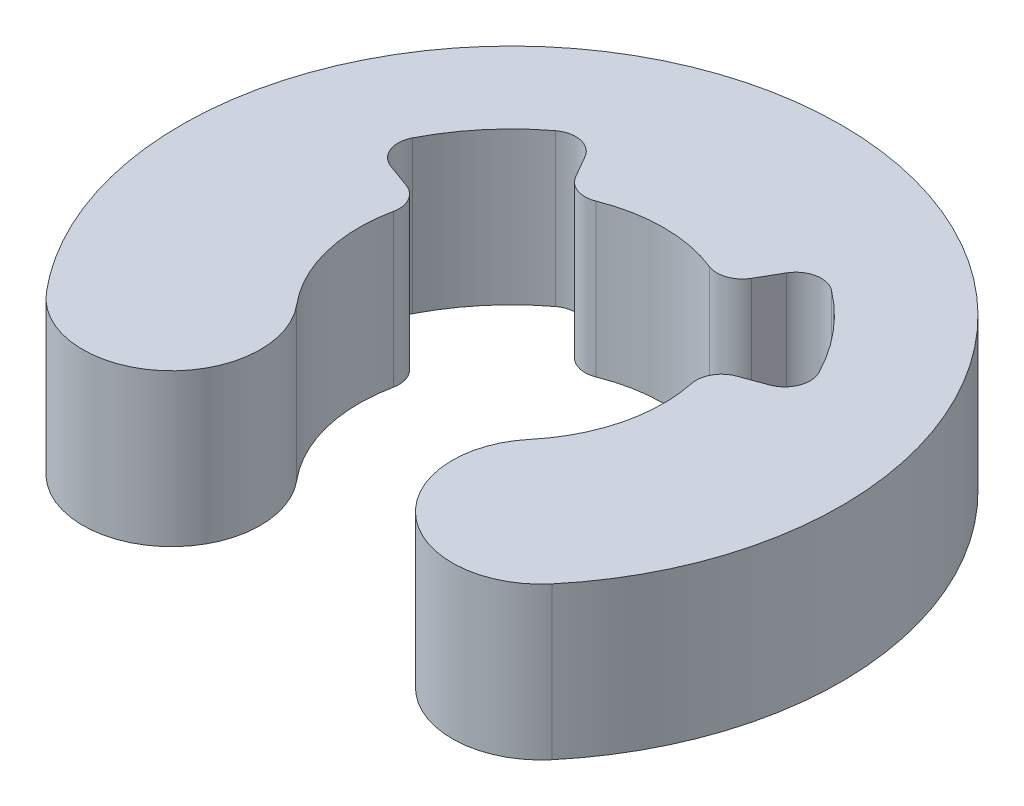
SolidWorks part; units mm, degrees
ref_plane "Plano frontal" through (0, 0, 0) normal (0, 0, 1) x (1, 0, 0)
ref_plane "Plano superior" through (0, 0, 0) normal (0, 1, 0) x (1, 0, 0)
ref_plane "Plano direito" through (0, 0, 0) normal (1, 0, 0) x (0, 0, -1)
sketch "Esboço1" plane through (0, 0, 0) normal (0, 1, 0) x (1, 0, 0)
  line L0 (0, 0) -> (0, 6.5) construction
  line L1 (0, 0) -> (-3.25, 5.6292) construction
  line L2 (0, 0) -> (-6.108, 2.2231) construction
  line L3 (0, 0) -> (-4.9793, -4.1781) construction
  line L4 (0, 0) -> (6.108, 2.2231) construction
  line L5 (0, 0) -> (3.25, 5.6292) construction
  line L6 (-3.7293, 1.3574) -> (-3.2552, 1.1848)
  line L7 (-1.9843, 3.4369) -> (-1.7321, 3)
  line L8 (1.9843, 3.4369) -> (1.7321, 3)
  line L9 (3.7293, 1.3574) -> (3.2552, 1.1848)
  arc A0 (4.9793, -4.1781) -> (-4.9793, -4.1781) centre (0, 0) ccw
  arc A1 (2.1408, -3.9581) -> (4.2698, -1.421) centre (0, 0) ccw construction
  arc A2 (2.2981, -1.9284) -> (2.9367, 0.6128) centre (0, 0) ccw
  arc A3 (-4.9793, -4.1781) -> (-2.2981, -1.9284) centre (-3.6387, -3.0532) ccw
  arc A4 (4.9793, -4.1781) -> (2.2981, -1.9284) centre (3.6387, -3.0532) cw
  arc A5 (-4.9793, -4.1781) -> (4.9793, -4.1781) centre (0, 0) ccw construction
  arc A6 (-2.1408, -3.9581) -> (2.1408, -3.9581) centre (0, 0) ccw construction
  arc A7 (0, 4.5) -> (-2.25, 3.8971) centre (0, 0) ccw construction
  arc A8 (-2.7195, 3.5853) -> (-4.0031, 2.0556) centre (0, 0) ccw
  arc A9 (2.25, 3.8971) -> (0, 4.5) centre (0, 0) ccw construction
  arc A10 (4.2698, -1.421) -> (4.2286, 1.5391) centre (0, 0) ccw construction
  arc A11 (4.0031, 2.0556) -> (2.7195, 3.5853) centre (0, 0) ccw
  arc A12 (-4.2286, 1.5391) -> (-4.2698, -1.421) centre (0, 0) ccw construction
  arc A13 (-3.4472, -2.8925) -> (-2.1408, -3.9581) centre (0, 0) ccw construction
  arc A14 (-4.2698, -1.421) -> (-3.4472, -2.8925) centre (0, 0) ccw construction
  arc A15 (2.2981, -1.9284) -> (4.2698, -1.421) centre (3.6387, -3.0532) cw construction
  arc A16 (4.2698, -1.421) -> (4.9793, -4.1781) centre (3.6387, -3.0532) cw construction
  arc A17 (-4.2698, -1.421) -> (-4.9793, -4.1781) centre (-3.6387, -3.0532) ccw construction
  arc A18 (-2.2981, -1.9284) -> (-4.2698, -1.421) centre (-3.6387, -3.0532) ccw construction
  arc A19 (-2.2981, -1.9284) -> (2.2981, -1.9284) centre (0, 0) ccw construction
  arc A20 (2.8191, 1.0261) -> (1.5, 2.5981) centre (0, 0) ccw construction
  arc A21 (1.1135, 2.7857) -> (-1.1135, 2.7857) centre (0, 0) ccw
  arc A22 (-1.5, 2.5981) -> (-2.8191, 1.0261) centre (0, 0) ccw construction
  arc A23 (-2.9367, 0.6128) -> (-2.2981, -1.9284) centre (0, 0) ccw
  arc A24 (3.2552, 1.1848) -> (2.9367, 0.6128) centre (3.4262, 0.7149) ccw
  arc A25 (4.0031, 2.0556) -> (3.7293, 1.3574) centre (3.5583, 1.8272) cw
  arc A26 (2.7195, 3.5853) -> (1.9843, 3.4369) centre (2.4173, 3.1869) ccw
  arc A27 (1.7321, 3) -> (1.1135, 2.7857) centre (1.299, 3.25) cw
  arc A28 (-1.7321, 3) -> (-1.1135, 2.7857) centre (-1.299, 3.25) ccw
  arc A29 (-3.2552, 1.1848) -> (-2.9367, 0.6128) centre (-3.4262, 0.7149) cw
  arc A30 (-4.0031, 2.0556) -> (-3.7293, 1.3574) centre (-3.5583, 1.8272) ccw
  arc A31 (-2.7195, 3.5853) -> (-1.9843, 3.4369) centre (-2.4173, 3.1869) cw
  dimension "D1" = 13
  dimension "D2" = 9
  dimension "D3" = 6
  dimension "D7" = 0.5
  dimension "D4" = 30
  dimension "D5" = 40
  dimension "D6" = 50
extrude "Ressalto-extrusão1" add sketch "Esboço1" along normal blind 3
